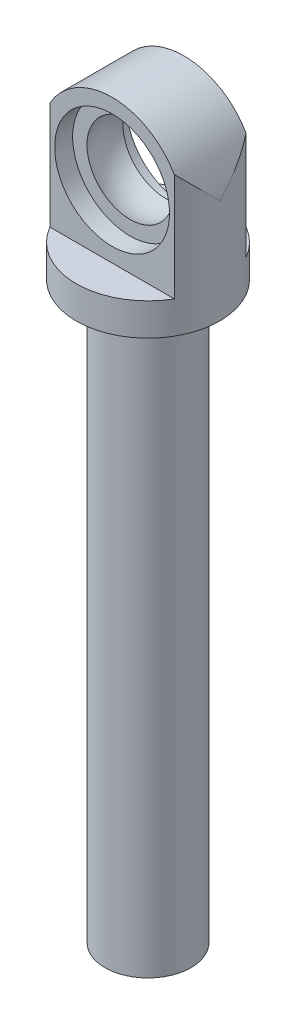
SolidWorks part; units mm, degrees
ref_plane "前视基准面" through (0, 0, 0) normal (0, 0, 1) x (1, 0, 0)
ref_plane "上视基准面" through (0, 0, 0) normal (0, 1, 0) x (1, 0, 0)
ref_plane "右视基准面" through (0, 0, 0) normal (1, 0, 0) x (0, 0, -1)
sketch "草图1" plane through (0, 0, 0) normal (0, 1, 0) x (1, 0, 0)
  circle A0 centre (0, 0) radius 10
  dimension "D1" = 20
extrude "凸台-拉伸1" add sketch "草图1" along normal blind 4.5
sketch "草图4" plane through (0, 0, 0) normal (0, 0, 1) x (1, 0, 0)
  line L0 (10, 4.5) -> (-10, 4.5) construction
  line L1 (-10, 4.5) -> (10, 4.5)
  line L2 (-10, 4.5) -> (-10, 14.5)
  line L4 (10, 4.5) -> (10, 14.5)
  line L5 (0, 193.283) -> (0, 138.3299) construction
  arc A0 (-10, 14.5) -> (10, 14.5) centre (0, 14.5) cw
  circle A1 centre (0, 14.5) radius 8
  dimension "D4" = 16
  dimension "D1" = 10
  dimension "D2" = 10
  dimension "D3" = 10
extrude "凸台-拉伸3" add sketch "草图4" against normal mid plane 10
sketch "草图5" plane through (0, 0, 0) normal (0, 0, 1) x (1, 0, 0)
  circle A0 centre (0, 14.5) radius 8
extrude "凸台-拉伸4" add sketch "草图5" along normal mid plane 5
ref_plane "基准面4" through (0, 0, 4.5) normal (0, 0, 1) x (1, 0, 0)
sketch "草图7" plane through (0, 0, 2.5) normal (0, 0, 1) x (1, 0, 0)
  circle A0 centre (0, 14.5) radius 6
  dimension "D1" = 12
sketch "草图8" plane through (0, 0, 4.5) normal (0, 0, 1) x (1, 0, 0)
  circle A0 centre (0, 14.5) radius 4
  dimension "D1" = 8
loft "放样1" add profiles "草图8", "草图7"
mirror "镜向1" about plane through (0, 0, 0) normal (0, 0, 1) of "放样1"
sketch "草图9" plane through (0, 4.5, 0) normal (0, 1, 0) x (1, 0, 0)
  circle A0 centre (0, 0) radius 10
  circle A1 centre (0, 0) radius 14.6272
extrude "切除-拉伸1" cut sketch "草图9" along normal blind 18
sketch "草图10" plane through (0, 0, 4.5) normal (0, 0, 1) x (1, 0, 0)
  circle A0 centre (0, 14.5) radius 2.5
  dimension "D1" = 5
extrude "切除-拉伸2" cut sketch "草图10" against normal blind 10
sketch "草图2" plane through (0, 0, 0) normal (0, -1, 0) x (1, 0, 0)
  circle A0 centre (0, 0) radius 6
  dimension "D2" = 12
extrude "凸台-拉伸5" add sketch "草图2" along normal blind 80 contours A0
sketch "草图11" plane through (0, 0, 4.5) normal (0, 0, 1) x (1, 0, 0)
  circle A0 centre (0, 14.5) radius 6
extrude "切除-拉伸3" cut sketch "草图11" against normal blind 36
sketch "草图12" plane through (0, 0, 0) normal (0, 0, 1) x (1, 0, 0)
  line L0 (0, 8) -> (0, 21)
  arc A0 (0, 8) -> (0, 21) centre (0, 14.5) ccw
  dimension "D1" = 13
revolve "切除-旋转1" cut sketch "草图12" angle 360 about L0
